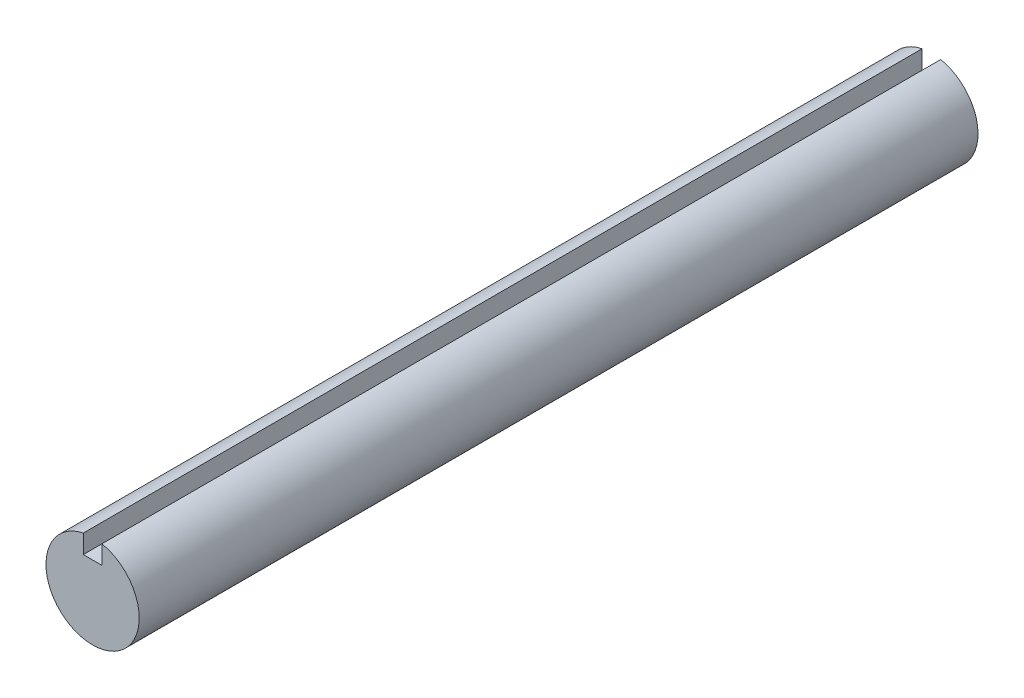
SolidWorks part; units mm, degrees
material "1060 Alloy"
ref_plane "Front Plane" through (0, 0, 0) normal (0, 0, 1) x (1, 0, 0)
ref_plane "Top Plane" through (0, 0, 0) normal (0, 1, 0) x (1, 0, 0)
ref_plane "Right Plane" through (0, 0, 0) normal (1, 0, 0) x (0, 0, -1)
sketch "Sketch1" plane through (0, 0, 0) normal (0, 0, 1) x (1, 0, 0)
  circle A0 centre (0, 0) radius 3.175
  dimension "D1" = 6.35
extrude "Boss-Extrude1" add sketch "Sketch1" along normal mid plane 57.15
sketch "Sketch2" plane through (0, 0, 28.575) normal (0, 0, 1) x (1, 0, 0)
  line L0 (-0.635, 3.1109) -> (-0.635, 1.8409)
  line L1 (-0.635, 1.8409) -> (0.635, 1.8409)
  line L2 (0.635, 1.8409) -> (0.635, 3.1109)
  circle A0 centre (0, 0) radius 3.175 construction
  arc A1 (-0.635, 3.1109) -> (0.635, 3.1109) centre (0, 0) cw
  point P6 (0, 1.8409)
  dimension "D3" = 3.175
  dimension "D1" = 1.27
  dimension "D2" = 1.27
extrude "Cut-Extrude1" cut sketch "Sketch2" against normal through all
